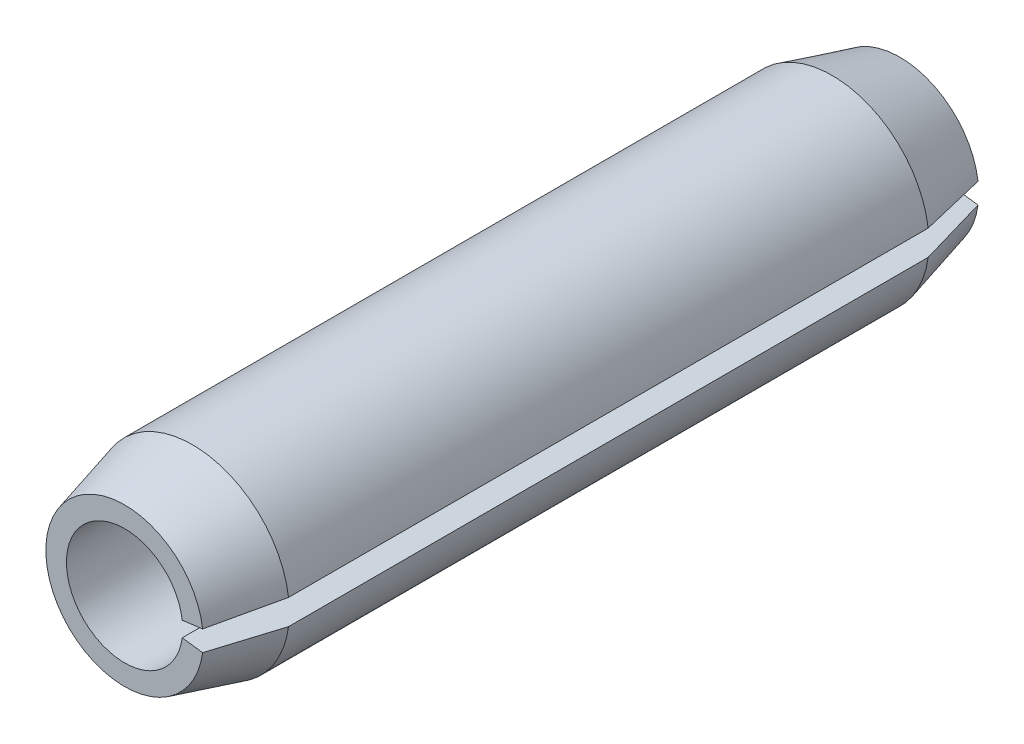
SolidWorks part; units mm, degrees
ref_plane "Přední rovina" through (0, 0, 0) normal (0, 0, 1) x (1, 0, 0)
ref_plane "Vrchní rovina" through (0, 0, 0) normal (0, 1, 0) x (1, 0, 0)
ref_plane "Pravá rovina" through (0, 0, 0) normal (1, 0, 0) x (0, 0, -1)
sketch "Skica1" plane through (0, 0, 0) normal (0, 0, 1) x (1, 0, 0)
  circle A0 centre (0, 0) radius 0.5
  circle A1 centre (0, 0) radius 0.3
  dimension "D" = 1
  dimension "s" = 0.2
extrude "Vysunout1" add sketch "Skica1" along normal mid plane 4
chamfer "Zkosit1" distance 0.35 angle 15 2 edges at (0.5, 0, -2) (0.5, 0, 2)
sketch "Skica2" plane through (0, 0, 2) normal (0, 0, 1) x (1, 0, 0)
  line L0 (0, 0) -> (0.5, 0) construction
  line L1 (0.4957, 0.0653) -> (0, 0)
  line L2 (0, 0) -> (0.4957, -0.0653)
  circle A0 centre (0, 0) radius 0.5 construction
  arc A1 (0.4957, 0.0653) -> (0.4957, -0.0653) centre (0, 0) cw
  dimension "D1" = 15
extrude "Odebrat vysunutím1" cut sketch "Skica2" against normal through all
